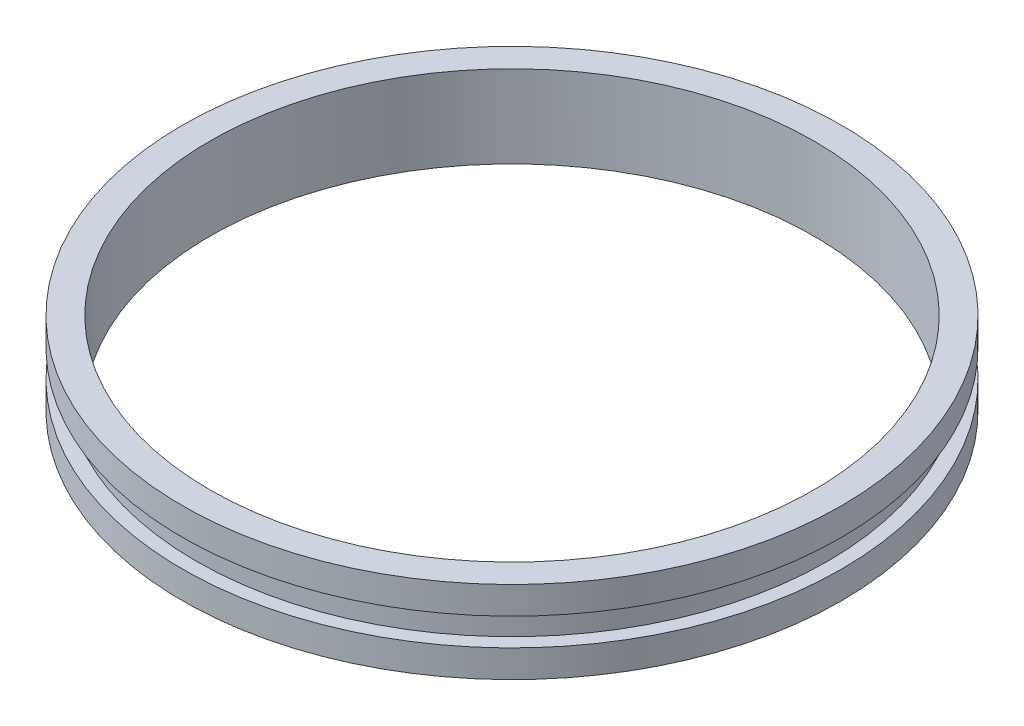
SolidWorks part; units mm, degrees
ref_plane "Alzado" through (0, 0, 0) normal (0, 0, 1) x (1, 0, 0)
ref_plane "Planta" through (0, 0, 0) normal (0, 1, 0) x (1, 0, 0)
ref_plane "Vista lateral" through (0, 0, 0) normal (1, 0, 0) x (0, 0, -1)
sketch "Croquis1" plane through (0, 0, 0) normal (0, 1, 0) x (1, 0, 0)
  circle A0 centre (0, 0) radius 6
  circle A1 centre (0, 0) radius 5.5
  dimension "D1" = 12
  dimension "D2" = 11
sketch "Croquis2" plane through (0, 0, 0) normal (0, 0, 1) x (1, 0, 0)
  line L0 (0, 0) -> (6, 0)
  line L1 (6, 0) -> (-6, 0) construction
  line L2 (6, 0) -> (6, -0.5)
  line L3 (6, -0.5) -> (5.75, -0.5)
  line L4 (5.75, -0.5) -> (5.75, -1)
  line L5 (5.75, -1) -> (6, -1)
  line L6 (6, -1) -> (6, -1.5)
  line L7 (6, -1.5) -> (0, -1.5)
  line L8 (0, -1.5) -> (0, 0)
  dimension "D1" = 6
  dimension "D2" = 0.5
  dimension "D3" = 0.25
  dimension "D4" = 0.5
  dimension "D5" = 0.5
revolve "Revolución1" add sketch "Croquis2" angle 360 about L8
extrude "Cortar-Extruir1" cut sketch "Croquis1" against normal blind 10 contours A1
